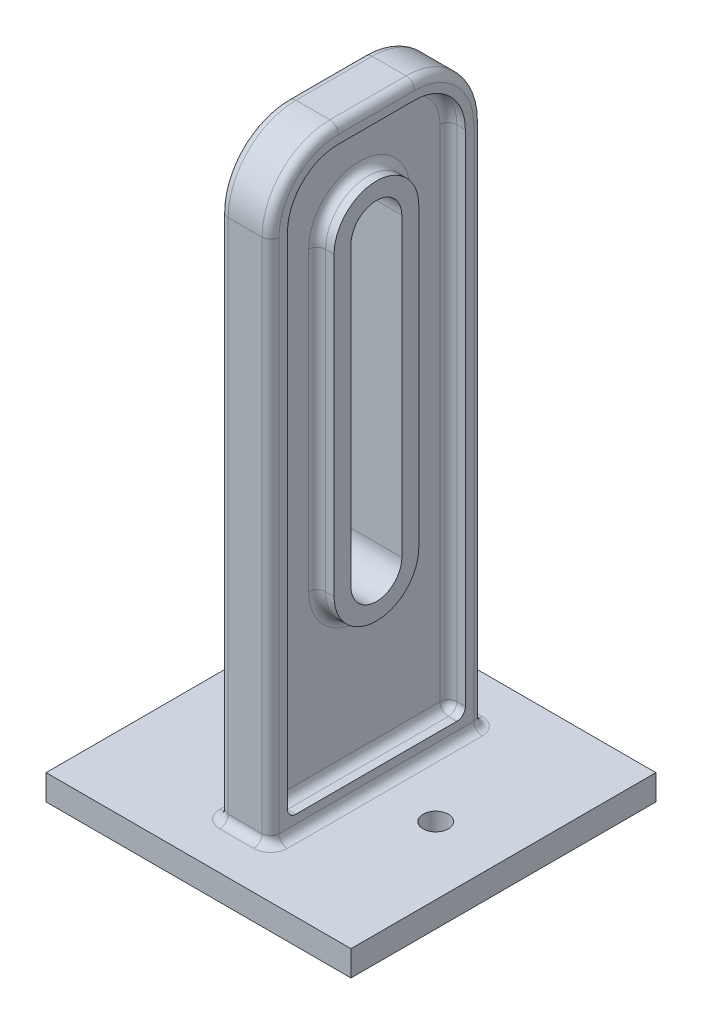
SolidWorks part; units mm, degrees
ref_plane "Front Plane" through (0, 0, 0) normal (0, 0, 1) x (1, 0, 0)
ref_plane "Top Plane" through (0, 0, 0) normal (0, 1, 0) x (1, 0, 0)
ref_plane "Right Plane" through (0, 0, 0) normal (1, 0, 0) x (0, 0, -1)
sketch "Sketch1" plane through (0, 0, 0) normal (0, 1, 0) x (1, 0, 0)
  line L1 (-18, -18) -> (18, -18)
  line L2 (-18, -18) -> (-18, 18)
  line L3 (-18, 18) -> (18, 18)
  line L4 (18, -18) -> (18, 18)
  line L5 (-18, -18) -> (18, 18) construction
  line L6 (-18, 18) -> (18, -18) construction
  point P0 (0, 0)
  dimension "D1" = 36
  dimension "D2" = 36
extrude "Boss-Extrude1" add sketch "Sketch1" along normal blind 3
sketch "Sketch2" plane through (0, 3, 0) normal (0, 1, 0) x (1, 0, 0)
  line L0 (0, 0) -> (10, 0) construction
  line L1 (10, 0) -> (0, 0) construction
  line L2 (0, 0) -> (-10, 0) construction
  circle A0 centre (10, 0) radius 1.5
  circle A1 centre (-10, 0) radius 1.5
  dimension "D3" = 3
  dimension "D4" = 3
  dimension "D1" = 10
  dimension "D2" = 10
extrude "Cut-Extrude1" cut sketch "Sketch2" against normal blind 3
sketch "Sketch3" plane through (0, 3, 0) normal (0, 1, 0) x (1, 0, 0)
  line L1 (-3, -12.5) -> (3, -12.5)
  line L2 (-3, -12.5) -> (-3, 12.5)
  line L3 (-3, 12.5) -> (3, 12.5)
  line L4 (3, -12.5) -> (3, 12.5)
  line L5 (-3, -12.5) -> (3, 12.5) construction
  line L6 (-3, 12.5) -> (3, -12.5) construction
  point P0 (0, 0)
  dimension "D1" = 6
  dimension "D2" = 25
extrude "Boss-Extrude2" add sketch "Sketch3" along normal blind 70
sketch "Sketch5" plane through (3, 0, 0) normal (1, 0, 0) x (0, 0, -1)
  line L0 (0, 60) -> (0, 25) construction
  line L1 (3, 60) -> (3, 25)
  line L2 (-3, 60) -> (-3, 25)
  line L3 (0, 73) -> (0, 63) construction
  line L4 (-12.5, 73) -> (12.5, 73) construction
  arc A0 (3, 60) -> (-3, 60) centre (0, 60) ccw
  arc A1 (-3, 25) -> (3, 25) centre (0, 25) ccw
  point P3 (0, 42.5)
  point P12 (0, 63)
  dimension "D1" = 3
  dimension "D2" = 35
  dimension "D3" = 10
extrude "Cut-Extrude2" cut sketch "Sketch5" against normal blind 70
fillet "Fillet1" radius 8 2 edges at (0, 73, -12.5) (0, 73, 12.5)
sketch "Sketch6" plane through (3, 0, 0) normal (1, 0, 0) x (0, 0, -1)
  line L8 (10.5, 5) -> (10.5, 65)
  line L9 (4.5, 71) -> (-4.5, 71)
  line L10 (-10.5, 65) -> (-10.5, 5)
  line L11 (-10.5, 5) -> (10.5, 5)
  line L12 (10.5, 5) -> (10.5, 65)
  line L13 (4.5, 71) -> (-4.5, 71)
  line L14 (-10.5, 65) -> (-10.5, 5)
  line L15 (-10.5, 5) -> (10.5, 5)
  line L20 (-5, 60) -> (-5, 25)
  line L21 (5, 25) -> (5, 60)
  line L22 (-5, 60) -> (-5, 25)
  line L23 (5, 25) -> (5, 60)
  arc A4 (10.5, 65) -> (4.5, 71) centre (4.5, 65) ccw
  arc A5 (-4.5, 71) -> (-10.5, 65) centre (-4.5, 65) ccw
  arc A6 (10.5, 65) -> (4.5, 71) centre (4.5, 65) ccw
  arc A7 (-4.5, 71) -> (-10.5, 65) centre (-4.5, 65) ccw
  arc A12 (-5, 25) -> (5, 25) centre (0, 25) ccw
  arc A13 (5, 60) -> (-5, 60) centre (0, 60) ccw
  arc A14 (-5, 25) -> (5, 25) centre (0, 25) ccw
  arc A15 (5, 60) -> (-5, 60) centre (0, 60) ccw
  dimension "D1" = 2
  dimension "D2" = 2
extrude "Cut-Extrude3" cut sketch "Sketch6" against normal blind 2
mirror "Mirror1" about plane through (0, 0, 0) normal (1, 0, 0) of "Cut-Extrude3"
fillet "Fillet3" radius 1 4 edges at (-1, 42.5, 5) (-1, 65, 0) (-1, 42.5, -5) (-1, 20, 0)
fillet "Fillet4" radius 1 5 edges at (-1, 35, -10.5) (-1, 35, 10.5) (-1, 69.2426, 8.7426) (-1, 71, 0) (-1, 69.2426, -8.7426)
fillet "Fillet5" radius 1 10 edges at (-3, 34, 12.5) (-3, 70.6569, 10.1569) (-3, 73, 0) (-3, 70.6569, -10.1569) (-3, 34, -12.5) (3, 34, 12.5) (3, 70.6569, 10.1569) (3, 73, 0) (3, 70.6569, -10.1569) (3, 34, -12.5)
fillet "Fillet6" radius 1 5 edges at (-2.5, 5, 10.5) (-1.2929, 5, 10.2071) (-2.5, 5, -10.5) (-1.2929, 5, -10.2071) (-1, 5, 0)
fillet "Fillet8" radius 1 8 edges at (2.7071, 3, -12.2071) (3, 3, 0) (2.7071, 3, 12.2071) (0, 3, 12.5) (-2.7071, 3, 12.2071) (-3, 3, 0) (-2.7071, 3, -12.2071) (0, 3, -12.5)
fillet "Fillet9" radius 1 1 edges at (1, 5, 0)
fillet "Fillet10" radius 1 4 edges at (1, 65, 0) (1, 42.5, -5) (1, 20, 0) (1, 42.5, 5)
fillet "Fillet11" radius 1 9 edges at (2.5, 5, 10.5) (1.2929, 5.2929, 10.5) (1, 35.5, 10.5) (1, 69.2426, 8.7426) (1, 71, 0) (1, 69.2426, -8.7426) (1, 35.5, -10.5) (2.5, 5, -10.5) (1.2929, 5.2929, -10.5)
